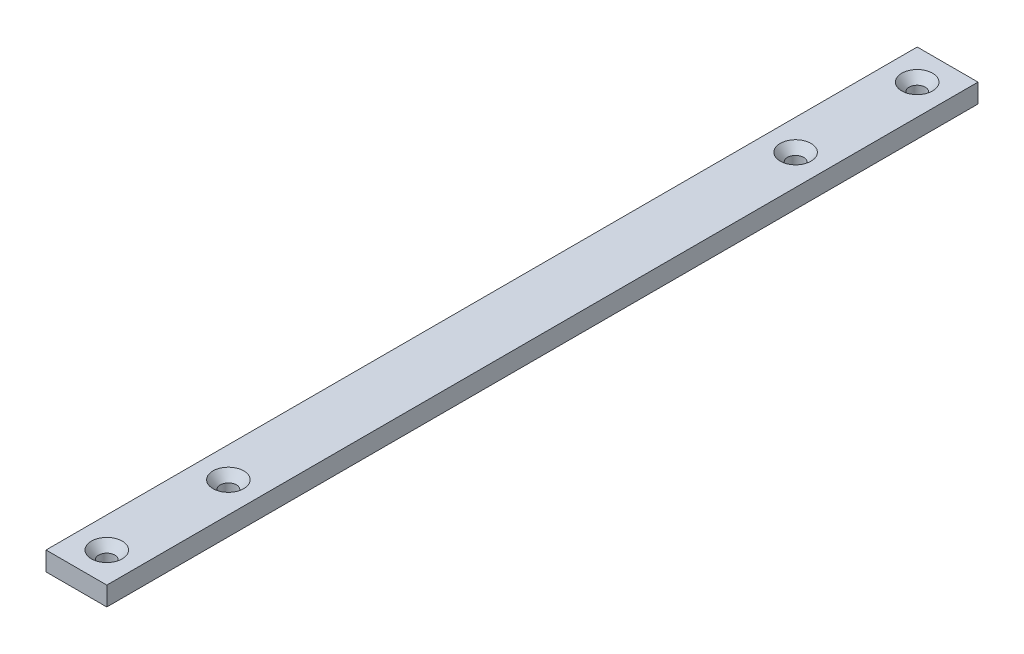
SolidWorks part; units mm, degrees
ref_plane "Front Plane" through (0, 0, 0) normal (0, 0, 1) x (1, 0, 0)
ref_plane "Top Plane" through (0, 0, 0) normal (0, 1, 0) x (1, 0, 0)
ref_plane "Right Plane" through (0, 0, 0) normal (1, 0, 0) x (0, 0, -1)
sketch "Sketch1" plane through (0, 0, 0) normal (0, 0, 1) x (1, 0, 0)
  line L0 (0, 3.9688) -> (0, -3.9688)
  line L1 (-12.7, 0) -> (12.7, 0) construction
  point P6 (0, 0)
  dimension "Width" = 25.4
  dimension "Thk" = 7.9375
sketch "Sketch2" plane through (0, 0, 0) normal (1, 0, 0) x (0, 0, -1)
  line L0 (152.4, 0) -> (-152.4, 0)
  point P4 (0, 0)
  dimension "Length" = 304.8
sketch "Sketch3" plane through (0, 0, 0) normal (0, 0, 1) x (1, 0, 0)
  line L1 (12.7, 3.9688) -> (-12.7, 3.9688)
  line L2 (12.7, 3.9688) -> (12.7, -3.9688)
  line L3 (12.7, -3.9688) -> (-12.7, -3.9688)
  line L4 (-12.7, 3.9688) -> (-12.7, -3.9688)
  line L5 (12.7, 3.9688) -> (-12.7, -3.9688) construction
  line L6 (12.7, -3.9688) -> (-12.7, 3.9688) construction
  point P0 (0, 0)
extrude "Boss-Extrude1" add sketch "Sketch3" along normal mid plane 364
sketch "Sketch5" plane through (0, 3.9688, 0) normal (0, 1, 0) x (1, 0, 0)
  line L0 (12.7, 182) -> (-12.7, 182) construction
  line L1 (12.7, 182) -> (12.7, -182) construction
  line L2 (12.7, 0) -> (-12.7, 0) construction
  circle A0 centre (0, 169.3) radius 3.5
  circle A1 centre (0, -169.3) radius 3.5
  circle A2 centre (0, 118.5) radius 3.5
  circle A3 centre (0, -118.5) radius 3.5
  dimension "D1" = 7
  dimension "D2" = 12.7
  dimension "D3" = 12.7
  dimension "D4" = 7
  dimension "D5" = 50.8
hole_wizard "CSK for 1/4 Flat Head Machine Screw1" positions "Sketch7" profile "Sketch8" countersink size "1/4" standard "ANSI Inch" end condition through all
sketch "Sketch7" plane through (0, 3.9688, 0) normal (0, 1, 0) x (1, 0, 0)
  point P0 (0, 169.3)
  point P3 (0, -169.3)
  point P6 (0, 118.5)
  point P9 (0, -118.5)
sketch "Sketch8" plane through (0, 3.9688, -169.3) normal (1, 0, 0) x (0, 0, 1)
  line L0 (0, 0) -> (0, 7.9375)
  line L1 (0, 7.9375) -> (3.3782, 7.9375)
  line L2 (3.3782, 7.9375) -> (3.3782, 3.5209)
  line L3 (3.3782, 3.5209) -> (6.4389, 0)
  line L5 (6.4389, 0) -> (0, 0)
  line L6 (-3.3782, 3.5209) -> (-6.4389, 0) construction
  line L11 (0, -6.35) -> (0, 107.95) construction
  dimension "Thru Hole Dia." = 6.7564
  dimension "Thru Hole Depth" = 7.9375
  dimension "Near C'Sink Dia." = 12.8778
  dimension "Near C'Sink Angle" = 82
